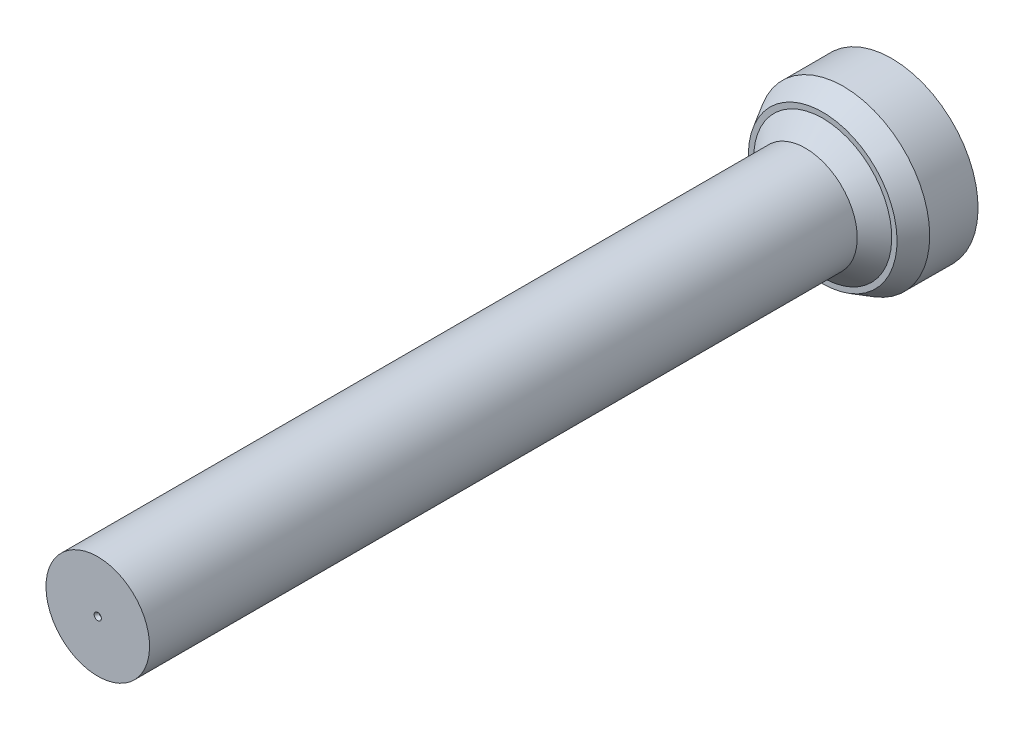
SolidWorks part; units mm, degrees
material "1.4301 (X5CrNi18-10)"
ref_plane "Vorne" through (0, 0, 0) normal (0, 0, 1) x (1, 0, 0)
ref_plane "Oben" through (0, 0, 0) normal (0, 1, 0) x (1, 0, 0)
ref_plane "Rechts" through (0, 0, 0) normal (1, 0, 0) x (0, 0, -1)
sketch "Skizze1" plane through (0, 0, 0) normal (1, 0, 0) x (0, 0, -1)
  line L0 (115, 0) -> (-115, 0) construction
  line L1 (115, 0) -> (115, 25)
  line L2 (115, 25) -> (95, 25)
  line L3 (95, 25) -> (95, 20)
  line L4 (95, 20) -> (90, 15)
  line L5 (90, 15) -> (-115, 15)
  line L6 (-115, 15) -> (-115, 0)
  line L7 (-233.986, 0) -> (93.6476, 0) construction
  line L8 (115, 0) -> (-115, 0)
  line L9 (-115, 12.5) -> (115, 12.5) construction
  line L10 (95, 25) -> (95, 12.5) construction
  arc A0 (89, 12.5) -> (95, 18.5) centre (89, 18.5) ccw construction
  point P11 (0, 0)
  dimension "D7" = 40
  dimension "D8" = 5
  dimension "D6" = 6
  dimension "D1" = 30
  dimension "D2" = 50
  dimension "D3" = 20
  dimension "D4" = 230
  dimension "D5" = 12.5
revolve "Rotation1" add sketch "Skizze1" angle 360 about L0
chamfer "Fase1" distance 6 angle 30 1 edges at (0, 25, -95)
sketch "Position" plane through (-0.0002, -1.3609, 115) normal (0, 0, 1) x (1, 0, 0)
  line L0 (-2.3515, 1.3609) -> (0.0002, 1.3609) construction
  line L1 (0.0002, 1.3609) -> (0.0002, -0.9908) construction
  circle A0 centre (0.0002, 1.3609) radius 2.3517
  circle A1 centre (0.0002, 1.3609) radius 15 construction
ref_plane "Ebene1" through (0, 0, 115) normal (0, -1, 0) x (1, 0, 0)
sketch "Skizze3" plane through (0, 0, 115) normal (0, -1, 0) x (1, 0, 0)
  line L0 (0, 0) -> (0, -4.7988) construction
  line L2 (0, -2.2004) -> (0.5, -1.9)
  line L3 (0.5, -1.9) -> (0.5, -0.9699)
  line L4 (0.5, -0.9699) -> (1.06, 0)
  line L5 (1.06, 0) -> (0, 0)
  line L6 (0, 0) -> (0, -2.2004)
  dimension "w1" = 30
  dimension "w2" = 59
  dimension "d1" = 1
  dimension "d2" = 2.12
  dimension "t1" = 1.9
revolve "Schnitt-Rotation1" cut sketch "Skizze3" angle 360 about L0
other "DIN 332 - A<1>"
